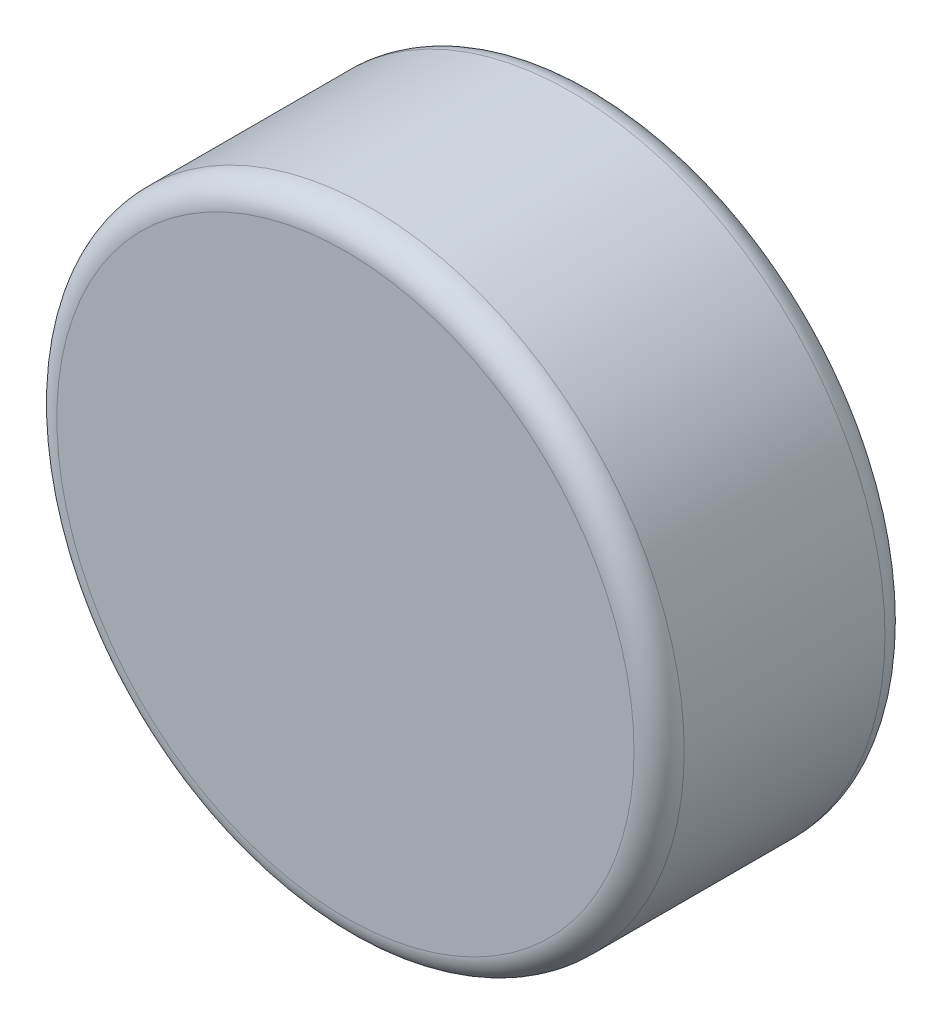
SolidWorks part; units mm, degrees
ref_plane "Front Plane" through (0, 0, 0) normal (0, 0, 1) x (1, 0, 0)
ref_plane "Top Plane" through (0, 0, 0) normal (0, 1, 0) x (1, 0, 0)
ref_plane "Right Plane" through (0, 0, 0) normal (1, 0, 0) x (0, 0, -1)
sketch "Sketch1" plane through (0, 0, 0) normal (0, 0, 1) x (1, 0, 0)
  circle A0 centre (0, 0) radius 3.175
  dimension "D1" = 6.35
extrude "Boss-Extrude1" add sketch "Sketch1" along normal blind 2.54
fillet "Fillet2" radius 0.254 1 edges at (3.175, 0, 0)
fillet "Fillet3" radius 0.254 1 edges at (3.175, 0, 2.54)
